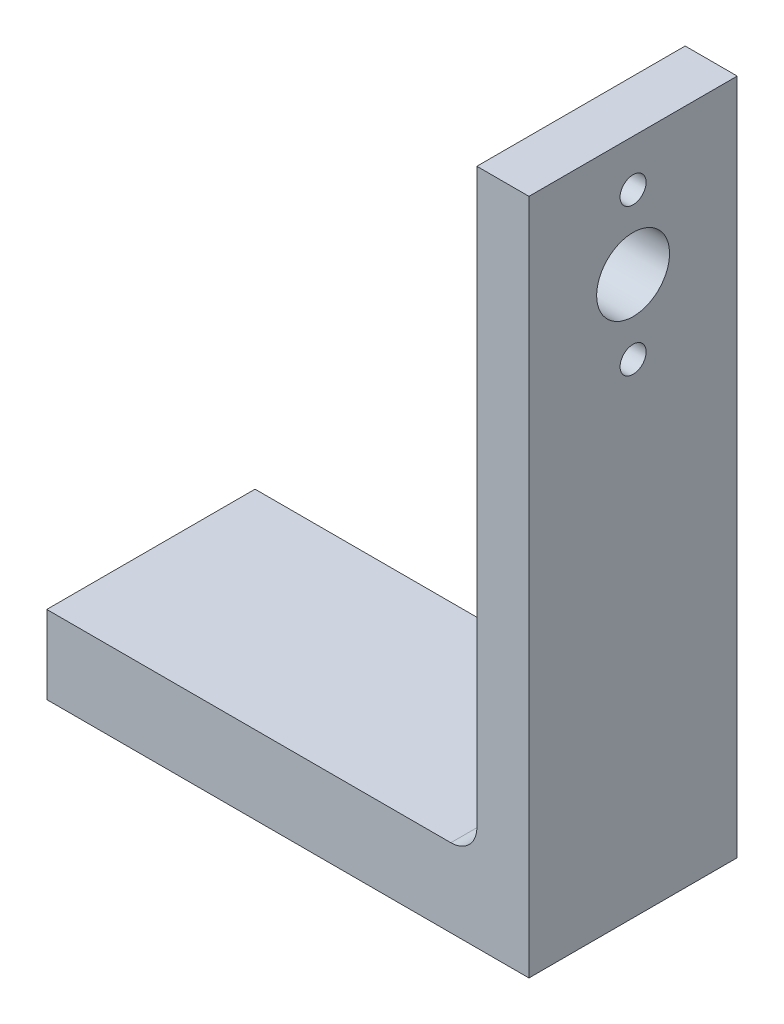
SolidWorks part; units mm, degrees
ref_plane "Front Plane" through (0, 0, 0) normal (0, 0, 1) x (1, 0, 0)
ref_plane "Top Plane" through (0, 0, 0) normal (0, 1, 0) x (1, 0, 0)
ref_plane "Right Plane" through (0, 0, 0) normal (1, 0, 0) x (0, 0, -1)
sketch "Sketch1" plane through (0, 0, 0) normal (0, 0, 1) x (1, 0, 0)
  line L1 (-57.15, -17.0351) -> (1.651, -17.0351)
  line L2 (-57.15, -17.0351) -> (-57.15, -7.5101)
  line L3 (-57.15, -7.5101) -> (-4.699, -7.5101)
  line L4 (1.651, -17.0351) -> (1.651, -7.5101)
  line L5 (1.651, -17.0351) -> (-14.859, -17.0351)
  line L6 (1.651, -17.0351) -> (1.651, 65.5149)
  line L7 (1.651, 65.5149) -> (-4.699, 65.5149)
  line L8 (-4.699, -7.5101) -> (-4.699, 65.5149)
  dimension "D1" = 9.525
  dimension "D2" = 6.35
  dimension "D3" = 58.801
  dimension "D4" = 82.55
extrude "Boss-Extrude1" add sketch "Sketch1" along normal blind 25.4 contours L6 L7 L8 L3 L2 L1
sketch "Sketch2" plane through (-4.699, 0, 0) normal (-1, 0, 0) x (0, 0, 1)
  line L1 (25.4, -7.5101) -> (0, -7.5101) construction
  line L2 (25.4, 65.5149) -> (0, 65.5149) construction
  circle A0 centre (12.7, 50.9099) radius 4.445
  circle A1 centre (12.7, 59.8634) radius 1.5875
  circle A2 centre (12.7, 41.9564) radius 1.5875
  point P8 (12.7, 65.5149)
  dimension "D1" = 17.907
  dimension "D2" = 8.9535
  dimension "D3" = 58.42
  dimension "D4" = 0
extrude "Cut-Extrude1" cut sketch "Sketch2" against normal through all
hole_wizard "#10-32 Tapped Hole1" positions "Sketch4" profile "Sketch3" tap size "#10-32" standard "ANSI Inch"
sketch "Sketch4" plane through (-57.15, 0, 0) normal (-1, 0, 0) x (0, 0, 1)
  line L2 (25.4, -7.5101) -> (0, -7.5101) construction
  point P0 (6.985, -12.2726)
  point P2 (18.415, -12.2726)
  point P10 (12.7, -7.5101)
  dimension "D1" = 11.43
  dimension "D2" = 5.715
sketch "Sketch3" plane through (-57.15, -12.2726, 6.985) normal (0, 1, 0) x (0, 0, 1)
  line L0 (0, 0) -> (0, 13.1513)
  line L1 (0, 13.1513) -> (2.0193, 11.938)
  line L2 (2.0193, 11.938) -> (2.0193, 0)
  line L5 (2.0193, 0) -> (0, 0)
  line L10 (0, 13.1513) -> (-2.0193, 11.938) construction
  line L11 (0, -6.35) -> (0, 107.95) construction
  dimension "Tap Drill Dia." = 4.0386
  dimension "Tap Drill Depth" = 11.938
  dimension "Drill Angle" = 118
cosmetic thread "Hole Thread1" parameters "D1"=9.652, "D2"=4.826
cosmetic thread "Hole Thread2" parameters "D1"=9.652, "D2"=4.826
fillet "Fillet1" radius 3.175 1 edges at (-4.699, -7.5101, 12.7)
